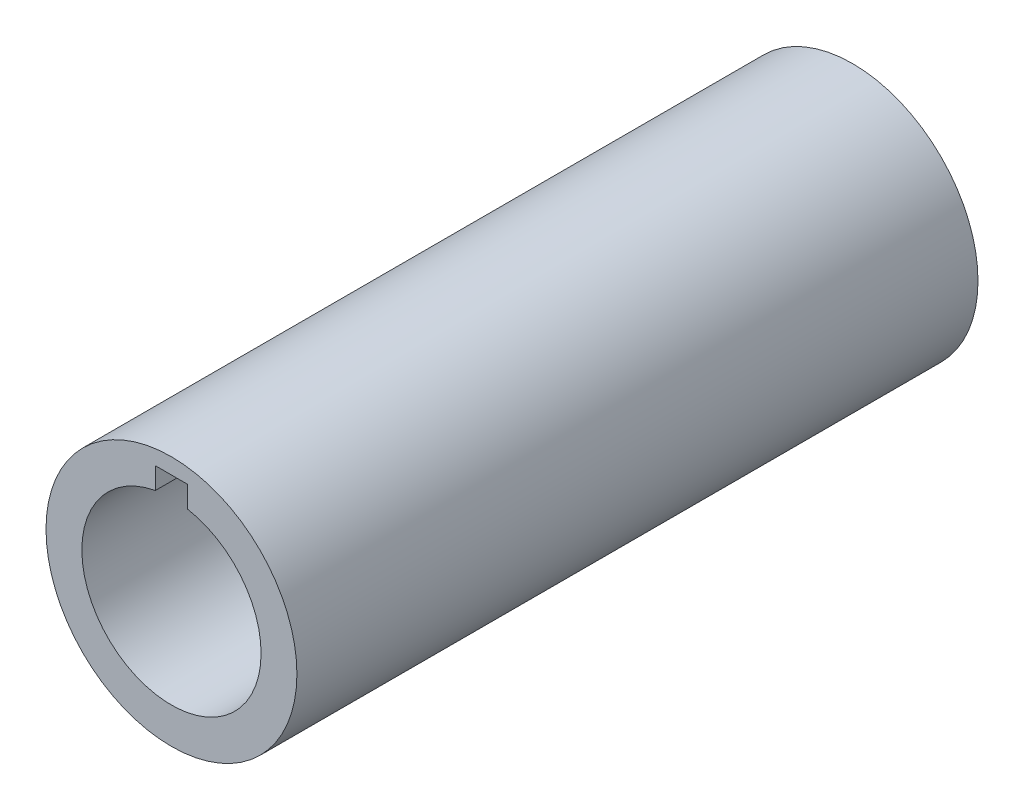
SolidWorks part; units mm, degrees
ref_plane "Alzado" through (0, 0, 0) normal (0, 0, 1) x (1, 0, 0)
ref_plane "Planta" through (0, 0, 0) normal (0, 1, 0) x (1, 0, 0)
ref_plane "Vista lateral" through (0, 0, 0) normal (1, 0, 0) x (0, 0, -1)
sketch "Croquis1" plane through (0, 0, 0) normal (0, 0, 1) x (1, 0, 0)
  line L0 (-55.5708, 46.4891) -> (-55.5708, 47.0891)
  line L5 (-55.5708, 47.0891) -> (-54.6708, 47.0891)
  line L6 (-54.6708, 47.0891) -> (-54.6708, 46.4891)
  arc A1 (-54.6708, 46.4891) -> (-55.5708, 46.4891) centre (-55.1208, 48.9482) ccw
  circle A2 centre (-55.1208, 48.9482) radius 3.5
  dimension "D1" = 5
  dimension "D2" = 7
  dimension "D4" = 0.6
extrude "Saliente-Extruir1" add sketch "Croquis1" along normal blind 8
sketch "Croquis2" plane through (0, 0, 8) normal (0, 0, 1) x (1, 0, 0)
  circle A0 centre (-55.1208, 48.9482) radius 3.5
extrude "Saliente-Extruir2" add sketch "Croquis2" along normal blind 1
sketch "Croquis3" plane through (0, 0, 9) normal (0, 0, 1) x (1, 0, 0)
  line L0 (-55.5708, 51.4074) -> (-55.5708, 52.0074)
  line L1 (-55.5708, 52.0074) -> (-54.6708, 52.0074)
  line L2 (-54.6708, 52.0074) -> (-54.6708, 51.4074)
  circle A0 centre (-55.1208, 48.9482) radius 3.5
  arc A1 (-55.5708, 51.4074) -> (-54.6708, 51.4074) centre (-55.1208, 48.9482) ccw
  dimension "D1" = 5
  dimension "D2" = 0.6
extrude "Saliente-Extruir3" add sketch "Croquis3" along normal blind 10
